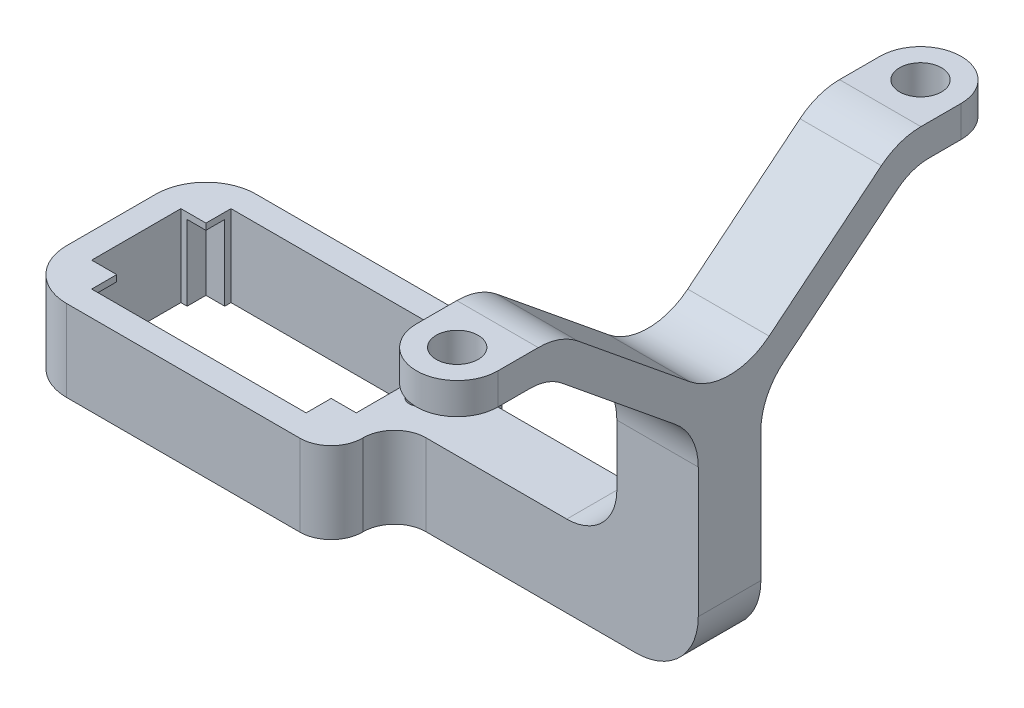
SolidWorks part; units mm, degrees
material "Nylon 101"
ref_plane "Front Plane" through (0, 0, 0) normal (0, 0, 1) x (1, 0, 0)
ref_plane "Top Plane" through (0, 0, 0) normal (0, 1, 0) x (1, 0, 0)
ref_plane "Right Plane" through (0, 0, 0) normal (1, 0, 0) x (0, 0, -1)
sketch "Sketch1" plane through (0, 20.13, 0) normal (0, 1, 0) x (1, 0, 0)
  line L0 (20.125, 10.125) -> (17.125, 10.125)
  line L1 (-20.125, 10.125) -> (-20.125, 7.125)
  line L2 (-20.125, -10.125) -> (-17.125, -10.125)
  line L3 (20.125, -10.125) -> (20.125, -7.125)
  line L4 (20.075, -10.075) -> (20.075, 10.075)
  line L5 (20.075, 10.075) -> (-20.075, 10.075)
  line L6 (-20.075, 10.075) -> (-20.075, -10.075)
  line L7 (-20.075, -10.075) -> (20.075, -10.075)
  line L10 (-20.075, 10.075) -> (-20.075, -10.075) construction
  line L12 (25.125, -15.125) -> (25.125, 15.125)
  line L13 (25.125, 15.125) -> (-25.125, 15.125)
  line L14 (-25.125, 15.125) -> (-25.125, -15.125)
  line L15 (-25.125, -15.125) -> (25.125, -15.125)
  line L16 (20.125, 7.125) -> (20.125, 10.125)
  line L17 (20.125, 7.125) -> (21.125, 7.125)
  line L19 (20.125, -7.125) -> (21.125, -7.125)
  line L20 (21.125, 7.125) -> (21.125, -7.125)
  line L21 (-20.125, 7.125) -> (-21.125, 7.125)
  line L23 (-20.125, -7.125) -> (-21.125, -7.125)
  line L24 (-21.125, 7.125) -> (-21.125, -7.125)
  line L26 (-17.125, 10.125) -> (-17.125, 11.125)
  line L27 (-17.125, 11.125) -> (17.125, 11.125)
  line L28 (17.125, 10.125) -> (17.125, 11.125)
  line L30 (17.125, -10.125) -> (17.125, -11.125)
  line L31 (17.125, -11.125) -> (-17.125, -11.125)
  line L32 (-17.125, -10.125) -> (-17.125, -11.125)
  line L33 (20.075, -10.075) -> (20.075, 10.075) construction
  line L34 (20.125, -10.125) -> (20.125, 10.125) construction
  line L35 (-20.075, -10.075) -> (20.075, -10.075) construction
  line L36 (17.125, -10.125) -> (20.125, -10.125)
  line L37 (-20.125, -10.125) -> (20.125, -10.125) construction
  line L38 (20.075, 10.075) -> (-20.075, 10.075) construction
  line L39 (-17.125, 10.125) -> (-20.125, 10.125)
  line L40 (20.125, 10.125) -> (-20.125, 10.125) construction
  line L41 (-20.125, -7.125) -> (-20.125, -10.125)
  line L42 (-20.125, 10.125) -> (-20.125, -10.125) construction
  dimension "D4" = 1
  dimension "D5" = 3
  dimension "D1" = 0
  dimension "D2" = 0.05
  dimension "D3" = 5
extrude "Boss-Extrude1" add sketch "Sketch1" against normal blind 12 and the other way blind 1
ref_plane "Plane1" through (0, 0, 0) normal (0, 0, 1) x (1, 0, 0)
sketch "Sketch2" plane through (0, 0, 0) normal (0, 0, 1) x (1, 0, 0)
  line L0 (25.125, 21.13) -> (60.625, 21.13)
  line L1 (60.625, 21.13) -> (60.625, 68.13)
  line L2 (60.625, 68.13) -> (73.625, 68.13)
  line L3 (73.625, 68.13) -> (73.625, 8.13)
  line L4 (73.625, 8.13) -> (25.125, 8.13)
  line L5 (25.125, 8.13) -> (25.125, 21.13) construction
  line L6 (25.125, 21.13) -> (25.125, 8.13)
  dimension "D1" = 48.5
  dimension "D2" = 60
extrude "Boss-Extrude2" add sketch "Sketch2" against normal mid plane 10
sketch "Sketch3" plane through (0, 68.13, 0) normal (0, 1, 0) x (1, 0, 0)
  line L0 (67.125, 37) -> (67.125, -37) construction
  line L1 (73.625, 37) -> (73.625, -37)
  line L2 (60.625, 37) -> (60.625, -37)
  line L3 (60.625, 5) -> (60.625, -5) construction
  line L6 (67.125, 5) -> (67.125, -5) construction
  line L7 (73.625, 5) -> (60.625, 5) construction
  line L8 (73.625, -5) -> (60.625, -5) construction
  line L9 (73.625, 5) -> (73.625, -5) construction
  line L10 (60.625, 5) -> (60.625, -5)
  line L11 (73.625, 5) -> (73.625, -5)
  arc A0 (73.625, 37) -> (60.625, 37) centre (67.125, 37) ccw
  arc A1 (60.625, -37) -> (73.625, -37) centre (67.125, -37) ccw
  point P2 (67.125, 0)
  point P7 (67.125, 0)
  line M8 (73.625, 5) -> (60.625, 5)
  line M10 (60.625, -5) -> (73.625, -5)
  dimension "D1" = 74
extrude "Boss-Extrude3" add sketch "Sketch3" against normal blind 5 contours L1 A0 L2 M8 | L2 A1 L1 M10
sketch "Sketch4" plane through (0, 63.13, 0) normal (0, -1, 0) x (1, 0, 0)
  circle A0 centre (67.125, 37) radius 3.35
  circle A1 centre (67.125, -37) radius 3.35
  dimension "D1" = 6.7
extrude "Cut-Extrude1" cut sketch "Sketch4" against normal blind 10
sketch "Sketch6" plane through (0, 21.13, 0) normal (0, 1, 0) x (1, 0, 0)
  line L0 (17.125, 11.125) -> (-17.125, 11.125) construction
  line L1 (21.125, 11.125) -> (17.125, 11.125)
  line L2 (21.125, 11.125) -> (21.125, 7.125)
  line L3 (21.125, 7.125) -> (17.125, 7.125)
  line L4 (17.125, 11.125) -> (17.125, 7.125)
  line L5 (21.125, -11.125) -> (17.125, -11.125)
  line L6 (21.125, -11.125) -> (21.125, -7.125)
  line L7 (21.125, -7.125) -> (17.125, -7.125)
  line L8 (17.125, -11.125) -> (17.125, -7.125)
  line L9 (-21.125, -11.125) -> (-17.125, -11.125)
  line L10 (-21.125, -11.125) -> (-21.125, -7.125)
  line L11 (-21.125, -7.125) -> (-17.125, -7.125)
  line L12 (-17.125, -11.125) -> (-17.125, -7.125)
  line L13 (-21.125, 11.125) -> (-17.125, 11.125)
  line L14 (-21.125, 11.125) -> (-21.125, 7.125)
  line L15 (-21.125, 7.125) -> (-17.125, 7.125)
  line L16 (-17.125, 11.125) -> (-17.125, 7.125)
  line L17 (21.125, -7.125) -> (21.125, 7.125) construction
  line L18 (-17.125, -11.125) -> (17.125, -11.125) construction
  line L19 (-21.125, 7.125) -> (-21.125, -7.125) construction
  line L20 (21.125, 7.125) -> (20.125, 7.125) construction
  line L21 (17.125, 10.125) -> (17.125, 11.125) construction
extrude "Boss-Extrude4" add sketch "Sketch6" against normal blind 1
sketch "Sketch10" plane through (0, 8.13, 0) normal (0, -1, 0) x (1, 0, 0)
  line L1 (21.125, 7.125) -> (21.125, -7.125) construction
  line L2 (21.125, 0) -> (24.125, 0) construction
  circle A0 centre (24.125, 0) radius 2
  circle A1 centre (24.125, 0) radius 3.5
  dimension "D1" = 4
  dimension "D2" = 7
  dimension "D3" = 1
hole_wizard "Tap Drill for M4x0.7 Tap1" positions "Sketch11" profile "Sketch12" hole size "M4x0.7" standard "ANSI Metric" end condition through all
sketch "Sketch11" plane through (0, 8.13, 0) normal (0, -1, 0) x (-1, 0, 0)
  point P0 (-24.125, 0)
sketch "Sketch12" plane through (24.125, 8.13, 0) normal (1, 0, 0) x (0, 0, -1)
  line L0 (0, 0) -> (0, 60)
  line L1 (0, 60) -> (1.65, 60)
  line L2 (1.65, 60) -> (1.65, 0.025)
  line L3 (1.65, 0.025) -> (1.675, 0)
  line L5 (1.675, 0) -> (0, 0)
  line L6 (-1.65, 0.025) -> (-1.675, 0) construction
  line L11 (0, -6.35) -> (0, 107.95) construction
  dimension "Thru Hole Dia." = 3.3
  dimension "Thru Hole Depth" = 60
  dimension "Near C'Sink Dia." = 3.35
  dimension "Near C'Sink Angle" = 90
sketch "Sketch13" plane through (0, 68.13, 0) normal (0, 1, 0) x (1, 0, 0)
  line L0 (60.625, 37) -> (60.625, -37) construction
  line L1 (60.625, 37) -> (60.625, -37)
  line L2 (73.625, 37) -> (73.625, -37) construction
  line L3 (73.625, 37) -> (73.625, -37)
  line L5 (60.625, -27) -> (73.625, -27)
  line L6 (60.625, -27) -> (60.625, 27)
  line L7 (60.625, 27) -> (73.625, 27)
  line L8 (73.625, -27) -> (73.625, 27)
  line L9 (60.625, -27) -> (73.625, 27) construction
  line L10 (60.625, 27) -> (73.625, -27) construction
  point P4 (67.125, 0)
  dimension "D1" = 10
  dimension "D2" = 10
extrude "Cut-Extrude2" cut sketch "Sketch13" against normal blind 22 contours L7 L1 L5 L3
sketch "Sketch14" plane through (73.625, 0, 0) normal (1, 0, 0) x (0, 0, -1)
  line L1 (27, 63.13) -> (27, 68.13)
  line L2 (27, 68.13) -> (0, 46.13)
  line L3 (-5, 46.13) -> (5, 46.13) construction
  line L8 (27, 63.13) -> (29, 63.13)
  line L9 (37, 63.13) -> (27, 63.13) construction
  line L10 (29, 63.13) -> (5, 43.5744)
  line L11 (5, 8.13) -> (5, 46.13) construction
  line L12 (5, 43.5744) -> (-5, 43.5744)
  line L13 (0, 43.5744) -> (0, 46.13)
  line L14 (-29, 63.13) -> (-5, 43.5744)
  line L15 (-27, 63.13) -> (-29, 63.13)
  line L16 (-27, 68.13) -> (0, 46.13)
  line L17 (-27, 63.13) -> (-27, 68.13)
  line M2 (5, 46.13) -> (-5, 46.13)
  line M3 (-5, 46.13) -> (-5, 8.13)
  line M5 (5, 8.13) -> (5, 46.13)
  dimension "D1" = 2
extrude "Boss-Extrude5" add sketch "Sketch14" against normal up to surface (13 mm away) contours L10 L8 L1 L2 M2 M5 | L17 L15 L14 L16 M3 M2 up to face at (60.625, 33.63, 0)
fillet "Fillet1" radius 10 6 edges at (73.625, 8.13, 0) (67.125, 43.5744, -5) (67.125, 46.13, 0) (67.125, 68.13, -27) (67.125, 43.5744, 5) (67.125, 68.13, 27)
fillet "Fillet2" radius 8 2 edges at (67.125, 63.13, 29) (67.125, 63.13, -29)
fillet "Fillet3" radius 5 4 edges at (25.125, 14.63, 15.125) (25.125, 14.63, 5) (25.125, 14.63, -15.125) (25.125, 14.63, -5)
fillet "Fillet4" radius 8 3 edges at (-25.125, 14.63, 15.125) (-25.125, 14.63, -15.125) (60.625, 21.13, 0)
